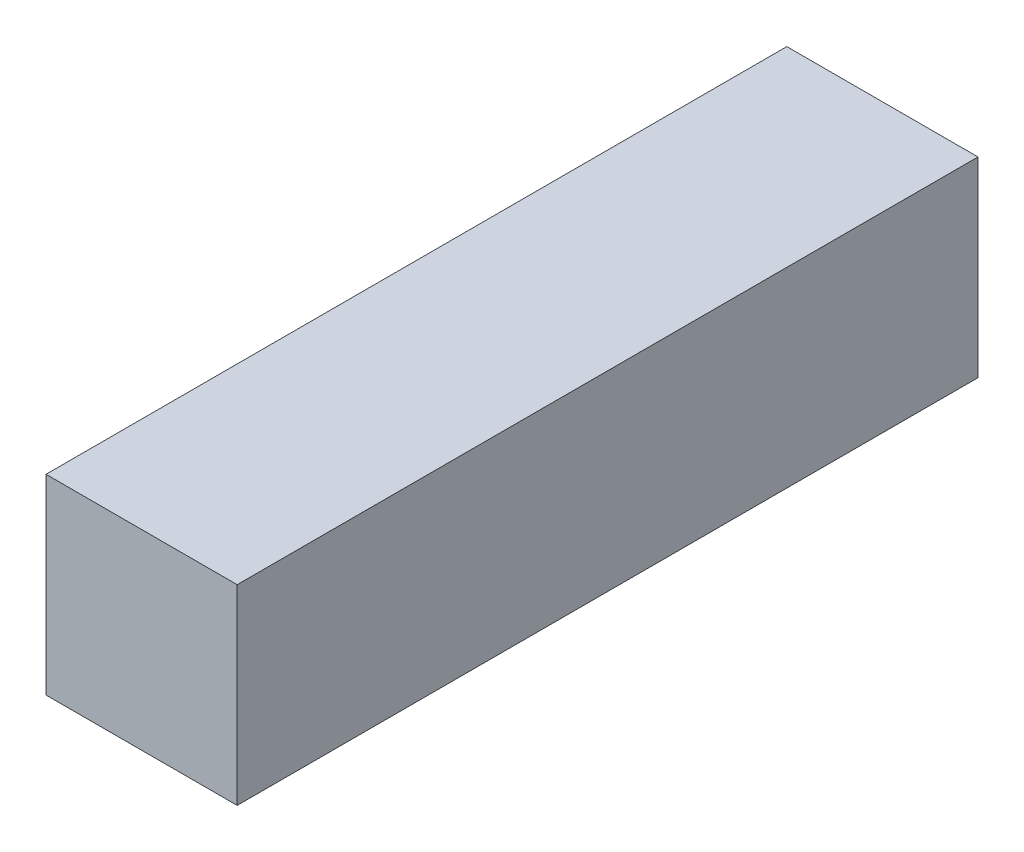
SolidWorks part; units mm, degrees
material "6061 Alloy"
ref_plane "Front Plane" through (0, 0, 0) normal (0, 0, 1) x (1, 0, 0)
ref_plane "Top Plane" through (0, 0, 0) normal (0, 1, 0) x (1, 0, 0)
ref_plane "Right Plane" through (0, 0, 0) normal (1, 0, 0) x (0, 0, -1)
sketch "Sketch1" plane through (0, 0, 0) normal (0, 1, 0) x (1, 0, 0)
  line L0 (-1, -7.25) -> (1, -7.25)
  line L1 (1, -7.25) -> (1, 7.25)
  line L2 (-2, 7.25) -> (-1, 7.25)
  line L3 (-1, 7.25) -> (-1, -7.25)
  line L4 (2, -7.25) -> (2, 7.25)
  line L5 (-2, 7.25) -> (-2, -8.25)
  line L6 (-2, -8.25) -> (1, -8.25)
  line L7 (2, -7.25) -> (2, -8.25)
  line L8 (2, -8.25) -> (1, -8.25)
  line L9 (1, 7.25) -> (2, 7.25)
  dimension "D1" = 1
  dimension "D2" = 1
extrude "Boss-Extrude1" add sketch "Sketch1" along normal blind 3
sketch "Sketch2" plane through (0, 3, 0) normal (0, 1, 0) x (1, 0, 0)
  line L0 (-2, 7.25) -> (2, 7.25)
  line L1 (2, 7.25) -> (2, -8.25)
  line L2 (2, -8.25) -> (-2, -8.25)
  line L3 (-2, -8.25) -> (-2, 7.25)
extrude "Boss-Extrude2" add sketch "Sketch2" along normal blind 1
sketch "Sketch3" plane through (0, 0, 0) normal (0, -1, 0) x (1, 0, 0)
  line L0 (-1, 7.25) -> (1, 7.25)
  line L1 (1, 7.25) -> (1, -7.25)
  line L2 (1, -7.25) -> (1.5, -7.25)
  line L3 (2, -7.25) -> (1, -7.25) construction
  line L4 (-1, 7.25) -> (-1, -7.25)
  line L5 (-1, -7.25) -> (-1.5, -7.25)
  line L6 (-1, -7.25) -> (-2, -7.25) construction
  line L7 (-1.5, -7.25) -> (-1.5, 7.7172)
  line L8 (-1.5, 7.7172) -> (1.5, 7.7172)
  line L9 (1.5, 7.7172) -> (1.5, -7.25)
extrude "Cut-Extrude1" cut sketch "Sketch3" against normal blind 0.25
extrude "Cut-Extrude7" cut sketch "Sketch9" against normal blind 6
sketch "Sketch9" plane through (31.1685, -3, 26.5462) normal (0, -1, 0) x (-0.7071, 0, 0.7071)
  line L2 (7.62, 34.2129) -> (9.8656, 36.4585)
  line L3 (9.8479, 36.4761) -> (-10.674, 56.998)
  line L4 (9.8479, 36.4761) -> (9.8656, 36.4585)
  line L5 (7.6028, 34.2311) -> (-12.919, 54.753)
  line L6 (-10.674, 56.998) -> (-12.919, 54.753)
  line L8 (7.62, 34.2129) -> (7.6028, 34.2311)
